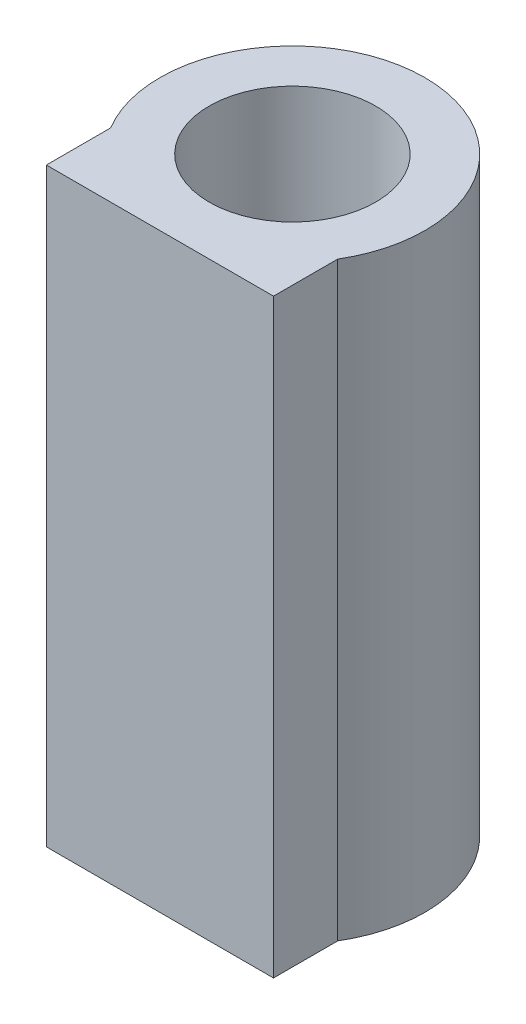
SolidWorks part; units mm, degrees
ref_plane "Front Plane" through (0, 0, 0) normal (0, 0, 1) x (1, 0, 0)
ref_plane "Top Plane" through (0, 0, 0) normal (0, 1, 0) x (1, 0, 0)
ref_plane "Right Plane" through (0, 0, 0) normal (1, 0, 0) x (0, 0, -1)
sketch "Sketch1" plane through (0, 0, 0) normal (0, 1, 0) x (1, 0, 0)
  line L1 (1.5, -1.75) -> (-1.5, -1.75)
  line L2 (1.5, -1.75) -> (1.5, 1.75)
  line L3 (1.5, 1.75) -> (-1.5, 1.75)
  line L4 (-1.5, -1.75) -> (-1.5, 1.75)
  line L5 (1.5, -1.75) -> (-1.5, 1.75) construction
  line L6 (1.5, 1.75) -> (-1.5, -1.75) construction
  circle A0 centre (0, 0) radius 1.75
  circle A1 centre (0, 0) radius 1.1
  point P0 (0, 0)
  dimension "2.2" = 2.2
  dimension "D1" = 3.5
  dimension "D2" = 3
extrude "Boss-Extrude1" add sketch "Sketch1" along normal blind 7.8 contours L2 A0 L4 A1 | L4 A0 | L2 A0 | A0 L1 L2 | A0 L4 L1
